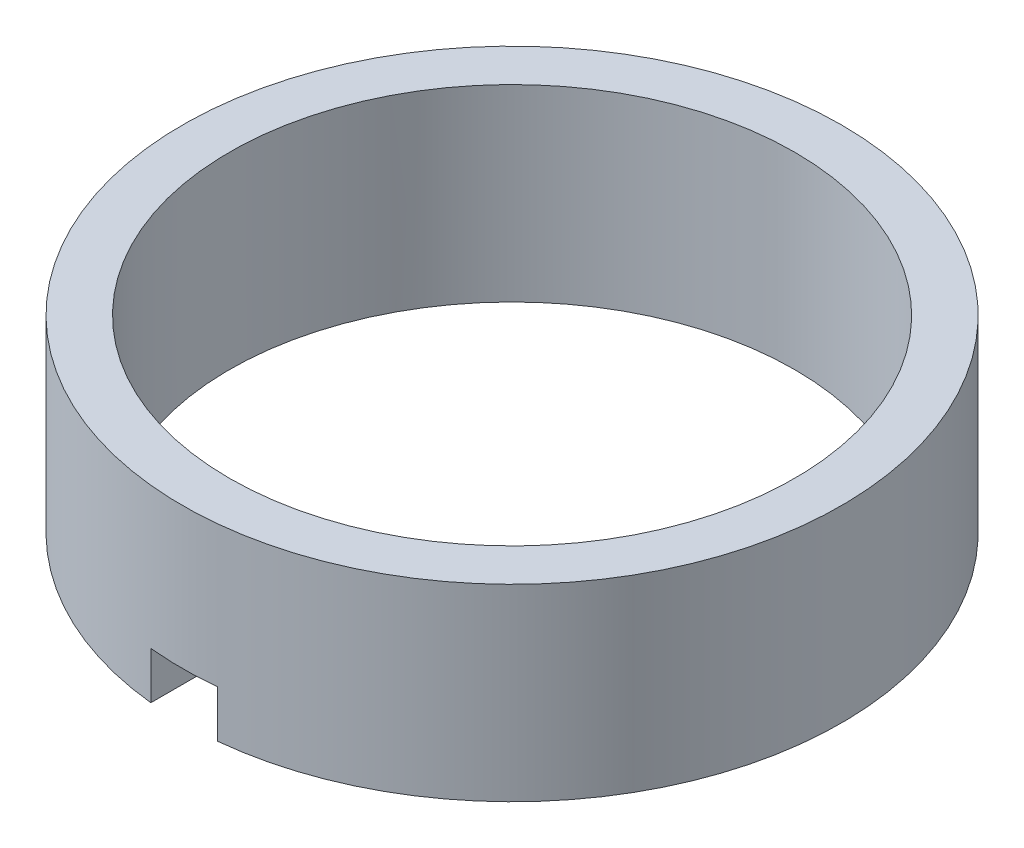
SolidWorks part; units mm, degrees
ref_plane "Front Plane" through (0, 0, 0) normal (1, 0, 0) x (0, 1, 0)
ref_plane "Top Plane" through (0, 0, 0) normal (0, 0, 1) x (0, 1, 0)
ref_plane "Right Plane" through (0, 0, 0) normal (0, 1, 0) x (-1, 0, 0)
sketch "Sketch1" plane through (0, 0, 0) normal (0, 0, 1) x (0, 1, 0)
  line L0 (-38.1, 133.35) -> (38.1, 133.35)
  line L1 (38.1, 133.35) -> (38.1, 114.3254)
  line L2 (38.1, 114.3254) -> (-38.1, 114.3254)
  line L3 (-38.1, 114.3254) -> (-38.1, 133.35)
  line L4 (-63.5, 0) -> (63.5, 0) construction
  point P6 (0, 0)
  dimension "D1" = 76.2
  dimension "D2" = 19.0246
  dimension "D3" = 133.35
  dimension "D4" = 38.1
revolve "Revolve1" add sketch "Sketch1" angle 360 about L4
sketch "Sketch2" plane through (0, 0, 0) normal (0, 1, 0) x (-1, 0, 0)
  line L1 (-13.4874, 0) -> (13.4874, 0)
  line L2 (-13.4874, 0) -> (-13.4874, 266.7)
  line L3 (-13.4874, 266.7) -> (13.4874, 266.7)
  line L4 (13.4874, 0) -> (13.4874, 266.7)
  point P8 (0, 0)
  dimension "D1" = 26.9748
  dimension "D2" = 266.7
extrude "Cut-Extrude2" cut sketch "Sketch2" along normal blind 19.05 from offset 38.1
